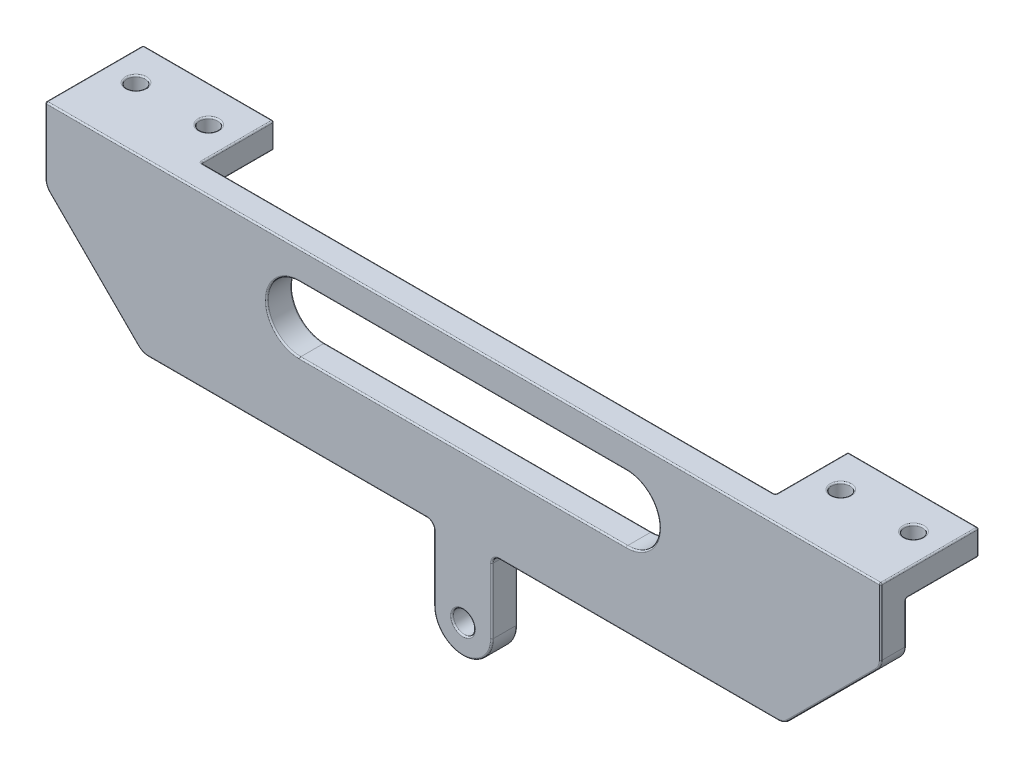
SolidWorks part; units mm, degrees
ref_plane "Front Plane" through (0, 0, 0) normal (0, 0, 1) x (1, 0, 0)
ref_plane "Top Plane" through (0, 0, 0) normal (0, 1, 0) x (1, 0, 0)
ref_plane "Right Plane" through (0, 0, 0) normal (1, 0, 0) x (0, 0, -1)
sketch "Sketch1" plane through (0, 0, 0) normal (0, 0, 1) x (1, 0, 0)
  line L0 (-100, 0) -> (100, 0) construction
  line L1 (-100, 0) -> (0, 100) construction
  line L2 (0, 100) -> (100, 0) construction
  line L3 (0, 0) -> (-50, 50) construction
  line L4 (-40, 60) -> (40, 60) construction
  line L5 (0, 100) -> (0, 60) construction
  circle A0 centre (-100, 0) radius 20
  circle A1 centre (0, 0) radius 20
  circle A2 centre (100, 0) radius 20
  point P4 (0, 0)
  dimension "D5" = 40
  dimension "D1" = 200
  dimension "D2" = 90
  dimension "D3" = 90
  dimension "D4" = 80
sketch "Sketch2" plane through (0, 0, 0) normal (0, 0, 1) x (1, 0, 0)
  line L0 (-56.5165, 43.4835) -> (-40, 60) construction
  line L1 (-100, 0) -> (0, 100) construction
  line L2 (-40, 60) -> (40, 60) construction
  line L3 (40, 60) -> (86.565, 13.435) construction
  line L4 (0, 100) -> (100, 0) construction
  line L5 (-49.4454, 36.4124) -> (-35.8579, 50)
  line L6 (-35.8579, 50) -> (35.8579, 50)
  line L7 (35.8579, 50) -> (79.4939, 6.364)
  line L8 (-63.5876, 50.5546) -> (-44.1421, 70)
  line L9 (-44.1421, 70) -> (44.1421, 70)
  line L10 (44.1421, 70) -> (93.636, 20.5061)
  line L11 (-63.5876, 50.5546) -> (-49.4454, 36.4124)
  line L12 (93.636, 20.5061) -> (79.4939, 6.364)
  line L13 (91.1612, 18.0312) -> (104.5962, 4.5962)
  line L14 (81.9688, 8.8388) -> (95.4038, -4.5962)
  line L15 (75.9584, 9.8995) -> (90.1005, 24.0416) construction
  line L16 (0, 100) -> (0, 60) construction
  line L17 (-6, 70) -> (-3.4532, 85.4203)
  line L18 (6, 70) -> (3.4532, 85.4203)
  circle A0 centre (100, 0) radius 3.5
  circle A1 centre (100, 0) radius 10 construction
  arc A2 (95.4038, -4.5962) -> (104.5962, 4.5962) centre (100, 0) ccw
  circle A3 centre (79.4939, 13.435) radius 1
  circle A4 centre (100, 0) radius 6.5 construction
  circle A5 centre (86.565, 20.5061) radius 1
  circle A6 centre (0, 60) radius 1.5
  circle A7 centre (0, 84.85) radius 1.5
  arc A8 (3.4532, 85.4203) -> (-3.4532, 85.4203) centre (0, 84.85) ccw
  circle A9 centre (-50, 50) radius 1.5
  circle A10 centre (0, 84.85) radius 3.5 construction
  point P25 (106.5, 0)
  point P47 (3.5, 82)
  dimension "D4" = 7
  dimension "D5" = 20
  dimension "D9" = 2
  dimension "D12" = 3
  dimension "D17" = 3
  dimension "D3" = 27.5
  dimension "D7" = 19
  dimension "D8" = 5
  dimension "D10" = 5
  dimension "D11" = 5
  dimension "D13" = 14.85
  dimension "D15" = 6
  dimension "D16" = 6
  dimension "D1" = 10
  dimension "D2" = 10
  dimension "D6" = 3
  dimension "D14" = 2
sketch "Sketch3" plane through (0, 0, 0) normal (0, 0, 1) x (1, 0, 0)
  line L0 (-100, 0) -> (100, 0) construction
  line L1 (-86.565, 13.435) -> (-50, 50) construction
  line L2 (-100, 0) -> (0, 100) construction
  line L3 (-50, 50) -> (-13.435, 13.435) construction
  line L4 (0, 0) -> (-50, 50) construction
  line L5 (-79.4939, 6.364) -> (-50, 35.8579)
  line L6 (-50, 35.8579) -> (-20.5061, 6.364)
  line L7 (-93.636, 20.5061) -> (-50, 64.1421)
  line L8 (-50, 64.1421) -> (-6.364, 20.5061)
  line L9 (-6.364, 20.5061) -> (-20.5061, 6.364)
  line L10 (-93.636, 20.5061) -> (-79.4939, 6.364)
  line L11 (-91.1612, 18.0312) -> (-104.5962, 4.5962)
  line L12 (-81.9688, 8.8388) -> (-95.4038, -4.5962)
  line L13 (-4.6576, -4.534) -> (-17.8509, 9.0191)
  line L14 (4.5962, 4.5962) -> (-8.8388, 18.0312)
  line L15 (-90.1005, 24.0416) -> (-75.9584, 9.8995) construction
  line L16 (-24.0416, 9.8995) -> (-9.8995, 24.0416) construction
  circle A0 centre (-100, 0) radius 3.5
  circle A1 centre (0, 0) radius 3.5
  circle A2 centre (-100, 0) radius 10 construction
  circle A3 centre (0, 0) radius 10 construction
  arc A4 (-4.6576, -4.534) -> (4.5962, 4.5962) centre (0, 0) ccw
  arc A5 (-104.5962, 4.5962) -> (-95.4038, -4.5962) centre (-100, 0) ccw
  circle A6 centre (0, 0) radius 20 construction
  circle A7 centre (-100, 0) radius 6.5 construction
  circle A8 centre (-86.565, 20.5061) radius 1
  circle A9 centre (0, 0) radius 6.5 construction
  circle A10 centre (-79.4939, 13.435) radius 1
  circle A11 centre (-20.5061, 13.435) radius 1
  circle A12 centre (-13.435, 20.5061) radius 1
  point P28 (-93.5, 0)
  point P36 (6.5, 0)
  dimension "D1" = 20
  dimension "D2" = 7
  dimension "D8" = 2
  dimension "D12" = 2
  dimension "D6" = 19
  dimension "D7" = 19
  dimension "D9" = 5
  dimension "D10" = 5
  dimension "D11" = 5
  dimension "D13" = 5
  dimension "D14" = 5
  dimension "D15" = 5
  dimension "D3" = 3
  dimension "D4" = 10
  dimension "D5" = 10
sketch "Sketch4" plane through (0, 0, 0) normal (0, 0, 1) x (1, 0, 0)
  line L0 (-57.5, 93.35) -> (57.5, 93.35)
  line L1 (4, 60) -> (4, 70)
  line L2 (57.5, 93.35) -> (57.5, 83.35)
  line L3 (57.5, 83.35) -> (44.1421, 70)
  line L4 (-44.1421, 70) -> (-57.5, 83.35)
  line L5 (-57.5, 83.35) -> (-57.5, 93.35)
  line L6 (-44.1421, 70) -> (44.1421, 70) construction
  line L7 (-4, 60) -> (-4, 70)
  line L8 (-22.5, 84.85) -> (22.5, 84.85) construction
  line L9 (-22.5, 89.35) -> (22.5, 89.35)
  line L10 (-22.5, 80.35) -> (22.5, 80.35)
  circle A2 centre (0, 60) radius 4
  arc A3 (-4, 60) -> (4, 60) centre (0, 60) ccw
  arc A4 (-22.5, 89.35) -> (-22.5, 80.35) centre (-22.5, 84.85) ccw
  arc A5 (22.5, 80.35) -> (22.5, 89.35) centre (22.5, 84.85) ccw
  point P4 (0, 100)
  point P14 (0, 84.85)
  point P27 (0, 93.35)
  dimension "D5" = 9
  dimension "D1" = 115
  dimension "D2" = 10
  dimension "D4" = 45
  dimension "D6" = 4
  dimension "D3" = 2.5
sketch "Sketch5" plane through (0, 0, 0) normal (0, 0, 1) x (1, 0, 0)
  line L0 (4, 60) -> (4, 70) construction
  line L1 (-4, 60) -> (-4, 70) construction
  line L2 (22.5, 89.35) -> (-22.5, 89.35)
  line L3 (-22.5, 80.35) -> (22.5, 80.35)
  line L4 (22.5, 89.35) -> (-22.5, 89.35)
  line L5 (-22.5, 80.35) -> (22.5, 80.35)
  line L6 (57.5, 83.35) -> (44.1421, 70) construction
  line L7 (57.5, 93.35) -> (57.5, 83.35) construction
  line L8 (-57.5, 93.35) -> (57.5, 93.35) construction
  line L9 (-57.5, 83.35) -> (-57.5, 93.35) construction
  line L10 (-44.1421, 70) -> (-57.5, 83.35) construction
  line L11 (4, 60) -> (4, 70)
  line L12 (-4, 60) -> (-4, 70)
  line L13 (57.5, 83.35) -> (44.1421, 70)
  line L14 (57.5, 93.35) -> (57.5, 83.35)
  line L15 (-57.5, 93.35) -> (57.5, 93.35)
  line L16 (-57.5, 83.35) -> (-57.5, 93.35)
  line L17 (-44.1421, 70) -> (-57.5, 83.35)
  line L18 (-44.1421, 70) -> (-4, 70)
  line L19 (4, 70) -> (44.1421, 70)
  arc A0 (-4, 60) -> (4, 60) centre (0, 60) ccw construction
  arc A1 (-4, 60) -> (4, 60) centre (0, 60) ccw
  arc A2 (22.5, 80.35) -> (22.5, 89.35) centre (22.5, 84.85) ccw
  arc A3 (-22.5, 89.35) -> (-22.5, 80.35) centre (-22.5, 84.85) ccw
  arc A4 (22.5, 80.35) -> (22.5, 89.35) centre (22.5, 84.85) ccw
  arc A5 (-22.5, 89.35) -> (-22.5, 80.35) centre (-22.5, 84.85) ccw
  circle A6 centre (0, 60) radius 1.5
  dimension "D1" = 0
extrude "Boss-Extrude1" add sketch "Sketch5" along normal blind 3.5
sketch "Sketch6" plane through (0, 93.35, 0) normal (0, 1, 0) x (1, 0, 0)
  line L0 (-57.5, 0) -> (-39.5, 0)
  line L1 (57.5, 0) -> (-57.5, 0) construction
  line L2 (-39.5, 0) -> (-39.5, 10)
  line L3 (-39.5, 10) -> (-57.5, 10)
  line L4 (-57.5, 10) -> (-57.5, 0)
  line L5 (-57.5, 5) -> (-39.5, 5) construction
  line L6 (-48.5, 10) -> (-48.5, 5) construction
  line L7 (0, 0) -> (0, 30.8482) construction
  line L8 (48.5, 10) -> (48.5, 5) construction
  line L9 (57.5, 5) -> (39.5, 5) construction
  line L10 (57.5, 10) -> (57.5, 0)
  line L11 (39.5, 10) -> (57.5, 10)
  line L12 (39.5, 0) -> (39.5, 10)
  line L13 (57.5, 0) -> (39.5, 0)
  circle A0 centre (-53.5, 5) radius 1.25
  circle A1 centre (-43.5, 5) radius 1.25
  circle A2 centre (43.5, 5) radius 1.25
  circle A3 centre (53.5, 5) radius 1.25
  dimension "D4" = 2.5
  dimension "D1" = 18
  dimension "D2" = 10
  dimension "D3" = 10
extrude "Boss-Extrude2" add sketch "Sketch6" against normal blind 3.5
fillet "Fillet1" radius 2 4 edges at (44.1421, 70, 1.75) (57.5, 83.35, 1.75) (-44.1421, 70, 1.75) (-57.5, 83.35, 1.75)
fillet "Fillet2" radius 1 2 edges at (-4, 70, 1.75) (4, 70, 1.75)
fillet "Fillet3" radius 0.2 69 edges at (-57.5, 89.85, -5) (0, 89.35, 3.5) (-57.5, 88.7644, 3.5) (-57.3476, 83.4131, 3.5) (-50.8208, 76.6748, 3.5) (-44.0791, 70.1521, 3.5) (-24.157, 70, 3.5) (-4.2929, 69.7071, 3.5) (-4, 64.5, 3.5) (24.157, 70, 3.5) (57.5, 91.6, -10) (39.5, 91.6, 0) (39.5, 91.6, -10) (57.5, 89.85, -5) (48.5, 89.85, 0) (48.5, 89.85, -10) (39.5, 93.35, -5) (48.5, 93.35, -10) (43.5, 89.85, -6.25) (43.5, 93.35, -6.25) (53.5, 89.85, -6.25) (53.5, 93.35, -6.25) (-43.5, 93.35, -3.75) (-43.5, 89.85, -3.75) (-53.5, 93.35, -3.75) (-53.5, 89.85, -3.75) (-39.5, 93.35, -5) (-39.5, 89.85, -5) (-48.5, 93.35, -10) (-48.5, 89.85, -10) (-48.5, 89.85, 0) (-39.5, 91.6, 0) (-39.5, 91.6, -10) (-57.5, 91.6, -10) (1.5, 60, 0) (1.5, 60, 3.5) (-27, 84.85, 0) (0, 80.35, 0) (27, 84.85, 0) (0, 89.35, 0) (-27, 84.85, 3.5) (0, 80.35, 3.5) (27, 84.85, 3.5) (0, 56, 0) (4, 64.5, 0) (24.157, 70, 0) (50.8208, 76.6748, 0) (57.5, 87.0144, 0) (0, 93.35, 0) (-57.5, 87.0144, 0) (-50.8208, 76.6748, 0) (-24.157, 70, 0) (-4, 64.5, 0) (0, 56, 3.5) (4, 64.5, 3.5) (50.8208, 76.6748, 3.5) (57.5, 88.7644, 3.5) (0, 93.35, 3.5) (-57.5, 93.35, -3.25) (57.5, 93.35, -3.25) (-57.3476, 83.4131, 0) (-44.0791, 70.1521, 0) (57.3476, 83.4131, 0) (44.0791, 70.1521, 0) (57.3476, 83.4131, 3.5) (44.0791, 70.1521, 3.5) (-4.2929, 69.7071, 0) (4.2929, 69.7071, 0) (4.2929, 69.7071, 3.5)
